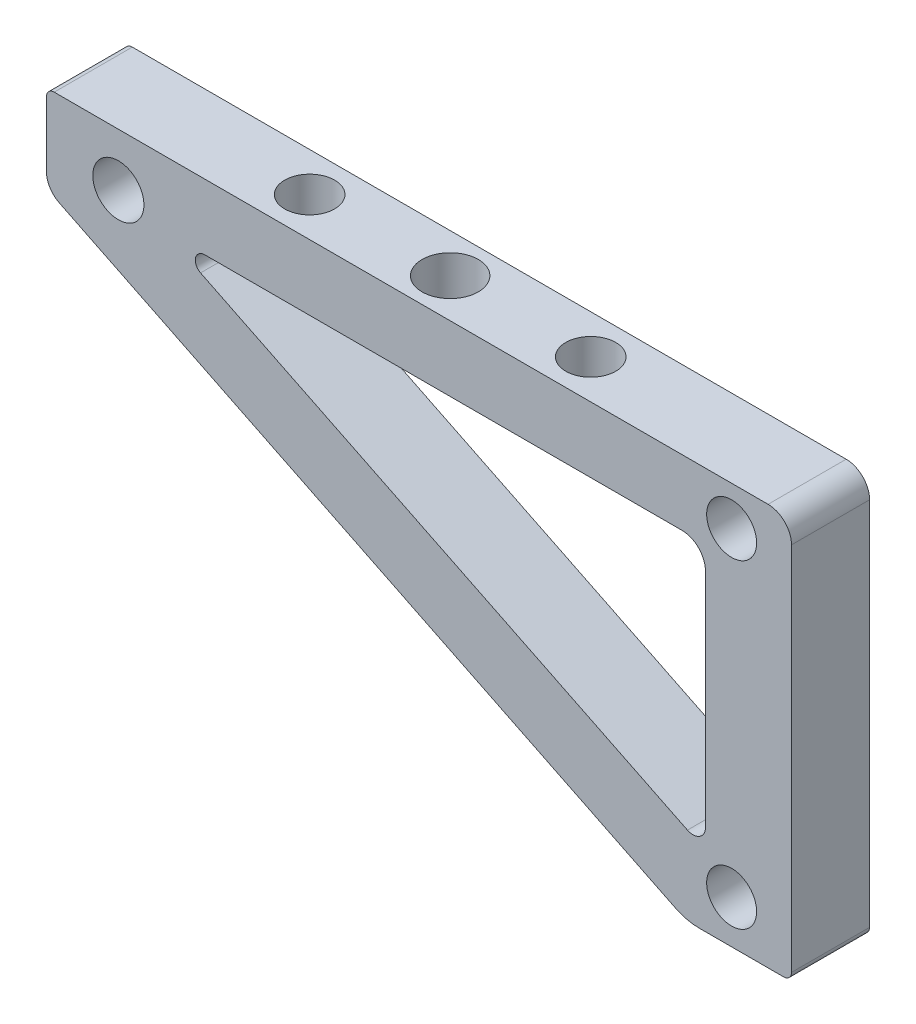
SolidWorks part; units mm, degrees
ref_plane "Front Plane" through (0, 0, 0) normal (0, 0, 1) x (1, 0, 0)
ref_plane "Top Plane" through (0, 0, 0) normal (0, 1, 0) x (1, 0, 0)
ref_plane "Right Plane" through (0, 0, 0) normal (1, 0, 0) x (0, 0, -1)
sketch "Sketch1" plane through (0, 0, 0) normal (0, 0, 1) x (1, 0, 0)
  line L2 (-39.7343, 17.0973) -> (-39.7343, 11.8396)
  line L12 (13.8585, -7.579) -> (13.8585, 10.4933)
  line L13 (20.8567, 15.8273) -> (20.8567, -14.2833)
  line L14 (18.9517, 17.7323) -> (-39.0993, 17.7323)
  line L15 (-38.669, 10.1297) -> (11.4117, -14.4632)
  line L16 (13.371, -14.9183) -> (20.2217, -14.9183)
  line L17 (12.3947, -8.491) -> (-27.1995, 10.9524)
  line L18 (11.9535, 12.3983) -> (-26.8636, 12.3983)
  arc A0 (-27.1995, 10.9524) -> (-26.8636, 12.3983) centre (-26.8636, 11.6363) cw
  arc A1 (12.3947, -8.491) -> (13.8585, -7.579) centre (12.8425, -7.579) ccw
  arc A2 (11.9535, 12.3983) -> (13.8585, 10.4933) centre (11.9535, 10.4933) cw
  arc A3 (11.4117, -14.4632) -> (13.371, -14.9183) centre (13.371, -10.4733) ccw
  arc A4 (-39.7343, 11.8396) -> (-38.669, 10.1297) centre (-37.8293, 11.8396) ccw
  arc A5 (-39.0993, 17.7323) -> (-39.7343, 17.0973) centre (-39.0993, 17.0973) ccw
  arc A6 (20.2217, -14.9183) -> (20.8567, -14.2833) centre (20.2217, -14.2833) ccw
  arc A7 (20.8567, 15.8273) -> (18.9517, 17.7323) centre (18.9517, 15.8273) ccw
  point P7 (-30.1596, 12.3983)
  point P8 (-30.0103, 12.3248)
  point P9 (13.8585, -9.2098)
  point P10 (0, 0)
  dimension "D7" = 12.3947
  dimension "D8" = 1.905
  dimension "D9" = 13.371
  dimension "D10" = 0.635
  dimension "D11" = 1.905
  dimension "D12" = 20.8567
  dimension "D13" = 26.8636
  dimension "D14" = 38.669
  dimension "D5" = 1.016
  dimension "D6" = 1.905
  dimension "D16" = 17.7323
  dimension "D4" = 0.762
  dimension "D2" = 4.445
  dimension "D18" = 0.635
  dimension "D3" = 11.4117
  dimension "D15" = 10.9524
  dimension "D17" = 10.1297
extrude "Boss-Extrude1" add sketch "Sketch1" along normal blind 6.35
sketch "Sketch5" plane through (0, 17.7323, 0) normal (0, 1, 0) x (1, 0, 0)
  line L0 (-39.0993, -3.175) -> (18.9517, -3.175) construction
  line L1 (-39.0993, -6.35) -> (-39.0993, 0) construction
  line L2 (18.9517, -6.35) -> (18.9517, 0) construction
  line L3 (-10.0738, -6.35) -> (-10.0738, 0) construction
  line L4 (18.9517, -6.35) -> (-39.0993, -6.35) construction
  line L5 (18.9517, 0) -> (-39.0993, 0) construction
  circle A0 centre (-21.5038, -3.175) radius 2.032
  circle A1 centre (1.3562, -3.175) radius 2.032
  dimension "D2" = 4.064
  dimension "D1" = 11.43
extrude "Cut-Extrude4" cut sketch "Sketch5" against normal blind 6.858
sketch "Sketch6" plane through (0, 17.7323, 0) normal (0, 1, 0) x (1, 0, 0)
  line L0 (-39.0993, -3.175) -> (18.9517, -3.175) construction
  line L1 (-39.0993, -6.35) -> (-39.0993, 0) construction
  line L2 (18.9517, -6.35) -> (18.9517, 0) construction
  line L3 (-10.0738, -6.35) -> (-10.0738, 0) construction
  line L4 (18.9517, -6.35) -> (-39.0993, -6.35) construction
  line L5 (18.9517, 0) -> (-39.0993, 0) construction
  circle A0 centre (-10.0738, -3.175) radius 2.286
  dimension "D1" = 4.572
extrude "Cut-Extrude5" cut sketch "Sketch6" against normal blind 6.858
sketch "Sketch7" plane through (0, 0, 0) normal (0, 0, -1) x (-1, 0, 0)
  circle A0 centre (33.8838, 13.4337) radius 2.079
  circle A1 centre (-15.9873, 14.5382) radius 2.032
  circle A2 centre (-15.9873, -11.4191) radius 2.032
  point P6 (-15.9873, -11.4191)
  dimension "D1" = 4.064
  dimension "D2" = 4.064
extrude "Cut-Extrude6" cut sketch "Sketch7" against normal through all
